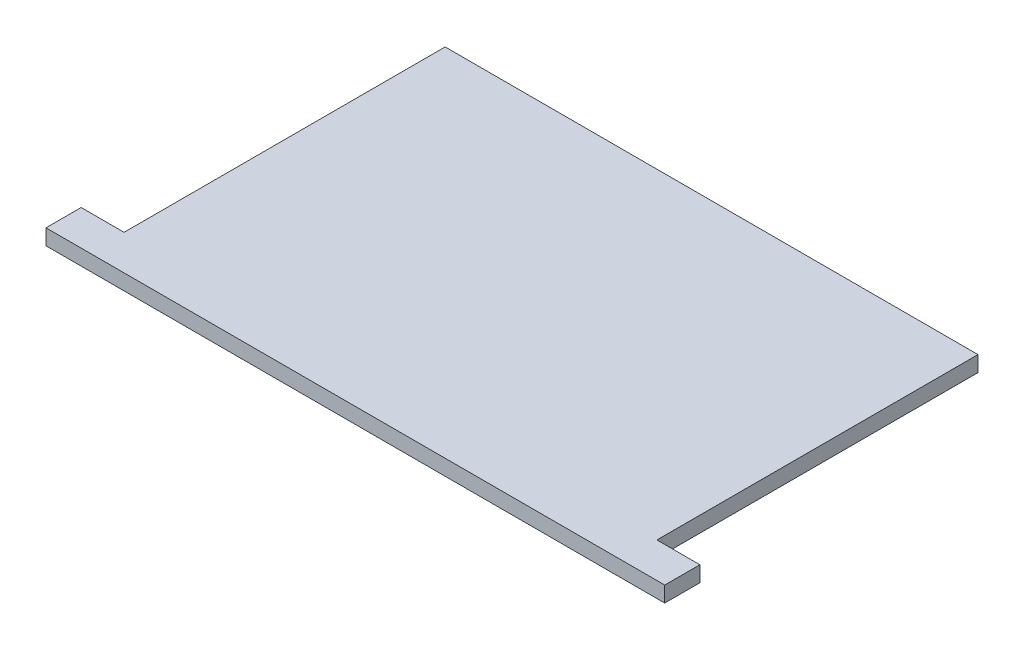
SolidWorks part; units mm, degrees
ref_plane "Front Plane" through (0, 0, 0) normal (0, 0, 1) x (1, 0, 0)
ref_plane "Top Plane" through (0, 0, 0) normal (0, 1, 0) x (1, 0, 0)
ref_plane "Right Plane" through (0, 0, 0) normal (1, 0, 0) x (0, 0, -1)
sketch "Sketch1" plane through (0, 0, 0) normal (0, 1, 0) x (1, 0, 0)
  line L1 (-158.5, -91.25) -> (158.5, -91.25)
  line L2 (-158.5, -91.25) -> (-158.5, 91.25)
  line L3 (-158.5, 91.25) -> (158.5, 91.25)
  line L4 (158.5, -91.25) -> (158.5, 91.25)
  line L5 (-158.5, -91.25) -> (158.5, 91.25) construction
  line L6 (-158.5, 91.25) -> (158.5, -91.25) construction
  point P0 (0, 0)
  dimension "D1" = 317
  dimension "D2" = 182.5
extrude "Boss-Extrude1" add sketch "Sketch1" along normal blind 8
sketch "Sketch3" plane through (0, 8, 0) normal (0, 1, 0) x (1, 0, 0)
  line L0 (-136.5, -73.25) -> (-136.5, 91.25)
  line L1 (-158.5, 91.25) -> (-158.5, -91.25) construction
  line L2 (-158.5, -73.25) -> (-136.5, -73.25)
  line L3 (158.5, 91.25) -> (-158.5, 91.25) construction
  line L6 (158.5, -91.25) -> (158.5, 91.25) construction
  line L7 (158.5, -73.25) -> (136.5, -73.25)
  line L10 (-136.5, 91.25) -> (-158.5, 91.25)
  line L11 (-158.5, 91.25) -> (-158.5, -73.25)
  line L13 (136.5, -73.25) -> (136.5, 91.25)
  line L14 (136.5, 91.25) -> (158.5, 91.25)
  line L15 (158.5, 91.25) -> (158.5, -73.25)
  dimension "D1" = 22
  dimension "D2" = 22
  dimension "D3" = 164.5
extrude "Cut-Extrude3" cut sketch "Sketch3" against normal through all
sketch "Sketch4" plane through (0, 0, 0) normal (0, -1, 0) x (1, 0, 0)
  line L1 (-136.5, -91.25) -> (136.5, -91.25)
  line L2 (-136.5, -91.25) -> (-136.5, 73.25)
  line L3 (-136.5, 73.25) -> (136.5, 73.25)
  line L4 (136.5, -91.25) -> (136.5, 73.25)
extrude "Cut-Extrude4" cut sketch "Sketch4" against normal blind 6
sketch "Sketch5" plane through (0, 6, 0) normal (0, -1, 0) x (1, 0, 0)
  line L0 (-158.5, 73.25) -> (158.5, 73.25) construction
  line L1 (-136.5, -91.25) -> (-116.5, -91.25)
  line L2 (-136.5, -91.25) -> (-136.5, 73.25)
  line L3 (-136.5, 73.25) -> (-116.5, 73.25)
  line L4 (-116.5, -91.25) -> (-116.5, 73.25)
  line L5 (-136.5, -91.25) -> (136.5, -91.25) construction
  line L6 (136.5, 73.25) -> (116.5, 73.25)
  line L7 (136.5, 73.25) -> (136.5, -91.25)
  line L8 (136.5, -91.25) -> (116.5, -91.25)
  line L9 (116.5, 73.25) -> (116.5, -91.25)
  dimension "D1" = 20
  dimension "D2" = 20
extrude "Boss-Extrude3" add sketch "Sketch5" along normal blind 6
